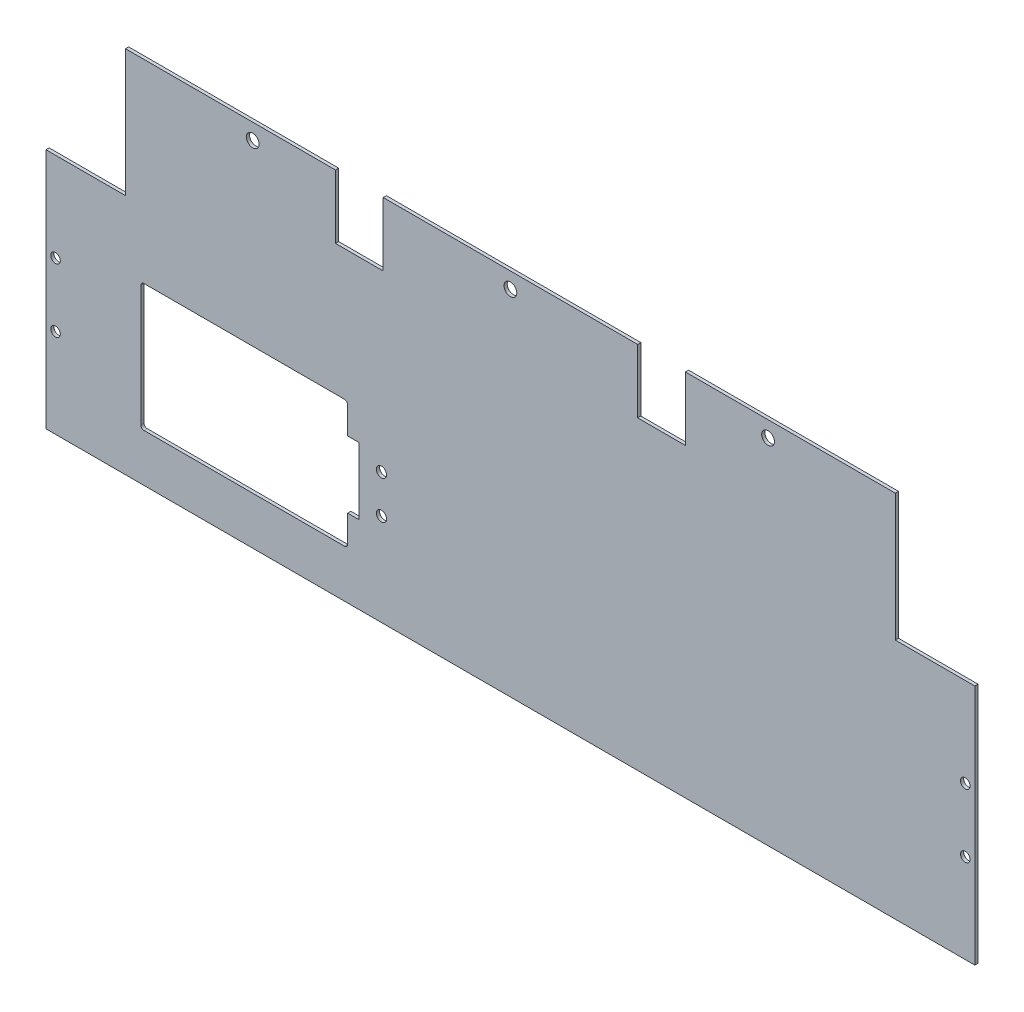
SolidWorks part; units mm, degrees
material "Thornel Mat VMA"
ref_plane "前视基准面" through (0, 0, 0) normal (0, 0, 1) x (1, 0, 0)
ref_plane "上视基准面" through (0, 0, 0) normal (0, 1, 0) x (1, 0, 0)
ref_plane "右视基准面" through (0, 0, 0) normal (1, 0, 0) x (0, 0, -1)
sketch "草图1" plane through (0, 0, 0) normal (0, 0, 1) x (1, 0, 0)
  line L0 (0, 0) -> (0, 76)
  line L1 (0, 76) -> (25, 76)
  line L2 (25, 76) -> (25, 116)
  line L3 (25, 116) -> (267, 116)
  line L4 (267, 116) -> (267, 76)
  line L5 (267, 76) -> (292, 76)
  line L6 (292, 76) -> (292, 0)
  line L7 (292, 0) -> (0, 0)
  line L8 (3, 48) -> (3, 28) construction
  line L9 (0, 38) -> (292, 38) construction
  line L10 (146, 116) -> (146, 0) construction
  line L11 (289, 48) -> (289, 28) construction
  circle A0 centre (3, 48) radius 1.5
  circle A1 centre (3, 28) radius 1.5
  circle A2 centre (289, 28) radius 1.5
  circle A3 centre (289, 48) radius 1.5
  point P13 (3, 38)
  dimension "D7" = 3
  dimension "D1" = 292
  dimension "D2" = 76
  dimension "D3" = 40
  dimension "D4" = 25
  dimension "D5" = 20
  dimension "D6" = 3
extrude "凸台-拉伸1" add sketch "草图1" along normal blind 1
sketch "草图2" plane through (0, 0, 1) normal (0, 0, 1) x (1, 0, 0)
  line L0 (146, 116) -> (146, 0) construction
  line L1 (267, 116) -> (25, 116) construction
  line L2 (0, 0) -> (292, 0) construction
  line L3 (186, 116) -> (186, 96)
  line L4 (91, 116) -> (106, 116)
  line L5 (91, 116) -> (91, 96)
  line L6 (91, 96) -> (106, 96)
  line L7 (106, 116) -> (106, 96)
  line L8 (201, 96) -> (186, 96)
  line L9 (201, 116) -> (201, 96)
  line L10 (201, 116) -> (186, 116)
  line L11 (25, 116) -> (25, 76) construction
  circle A0 centre (65, 111) radius 2
  circle A1 centre (227, 111) radius 2
  circle A2 centre (146, 111) radius 2
  point P14 (98.5, 116)
  point P15 (193.5, 116)
  dimension "D4" = 4
  dimension "D7" = 4
  dimension "D1" = 95
  dimension "D2" = 15
  dimension "D3" = 20
  dimension "D5" = 5
  dimension "D6" = 40
extrude "切除-拉伸1" cut sketch "草图2" against normal through all
sketch "草图3" plane through (0, 0, 0) normal (0, 0, -1) x (-1, 0, 0)
  line L0 (-37.4053, 34.9796) -> (-62.3303, 34.9796) construction
  line L1 (-94.8303, 54.9796) -> (-29.8303, 54.9796)
  line L2 (-94.8303, 54.9796) -> (-94.8303, 14.9796)
  line L3 (-94.8303, 14.9796) -> (-29.8303, 14.9796)
  line L4 (-82.5582, 20.8035) -> (-35.7082, 20.8035)
  line L5 (-34.2082, 22.3035) -> (-34.2082, 47.3035)
  line L6 (-35.7082, 48.8035) -> (-82.5582, 48.8035)
  line L7 (-84.0582, 47.3035) -> (-84.0582, 22.3035)
  line L11 (-84.0582, 47.3035) -> (-84.0582, 22.3035)
  line L12 (-29.8303, 54.9796) -> (-29.8303, 14.9796)
  line L13 (-94.8303, 54.9796) -> (-29.8303, 14.9796) construction
  line L14 (-94.8303, 14.9796) -> (-29.8303, 54.9796) construction
  line L15 (-62.3303, 34.9796) -> (-62.3303, 48.9796) construction
  arc A4 (-35.7082, 20.8035) -> (-34.2082, 22.3035) centre (-35.7082, 22.3035) ccw
  arc A5 (-34.2082, 47.3035) -> (-35.7082, 48.8035) centre (-35.7082, 47.3035) ccw
  arc A6 (-82.5582, 48.8035) -> (-84.0582, 47.3035) centre (-82.5582, 47.3035) ccw
  arc A7 (-84.0582, 22.3035) -> (-82.5582, 20.8035) centre (-82.5582, 22.3035) ccw
  arc A9 (-34.2082, 47.3035) -> (-35.7082, 48.8035) centre (-35.7082, 47.3035) ccw
  arc A10 (-82.5582, 48.8035) -> (-84.0582, 47.3035) centre (-82.5582, 47.3035) ccw
  arc A11 (-84.0582, 22.3035) -> (-82.5582, 20.8035) centre (-82.5582, 22.3035) ccw
  point P21 (-62.3303, 34.9796)
  dimension "D2" = 40
  dimension "D3" = 65
  dimension "D1" = 0
extrude "切除-拉伸5" cut sketch "草图3" against normal blind 10
sketch "草图4" plane through (0, 0, 0) normal (0, 0, -1) x (-1, 0, 0)
  line L0 (-94.8303, 34.9796) -> (-101.8303, 34.9796) construction
  line L1 (-94.8303, 54.9796) -> (-94.8303, 14.9796) construction
  line L2 (-98.3303, 24.4796) -> (-98.3303, 45.4796)
  line L3 (-98.3303, 45.4796) -> (-94.8303, 45.4796)
  line L4 (-94.8303, 45.4796) -> (-94.8303, 24.4796)
  line L5 (-98.3303, 24.4796) -> (-94.8303, 24.4796)
  point P9 (-98.3303, 34.9796)
  dimension "D1" = 3.5
  dimension "D2" = 21
extrude "切除-拉伸6" cut sketch "草图4" against normal blind 10
sketch "草图6" plane through (0, 0, 0) normal (0, 0, -1) x (-1, 0, 0)
  circle A0 centre (-105.4671, 28.9796) radius 1.6 construction
  circle A1 centre (-105.4671, 40.9796) radius 1.6 construction
  circle A2 centre (-105.4671, 28.9796) radius 1.6
  circle A3 centre (-105.4671, 40.9796) radius 1.6
extrude "切除-拉伸8" cut sketch "草图6" against normal blind 2
fillet "圆角1" radius 1 4 edges at (94.8303, 14.9796, 0.5) (29.8303, 14.9796, 0.5) (29.8303, 54.9796, 0.5) (94.8303, 54.9796, 0.5)
